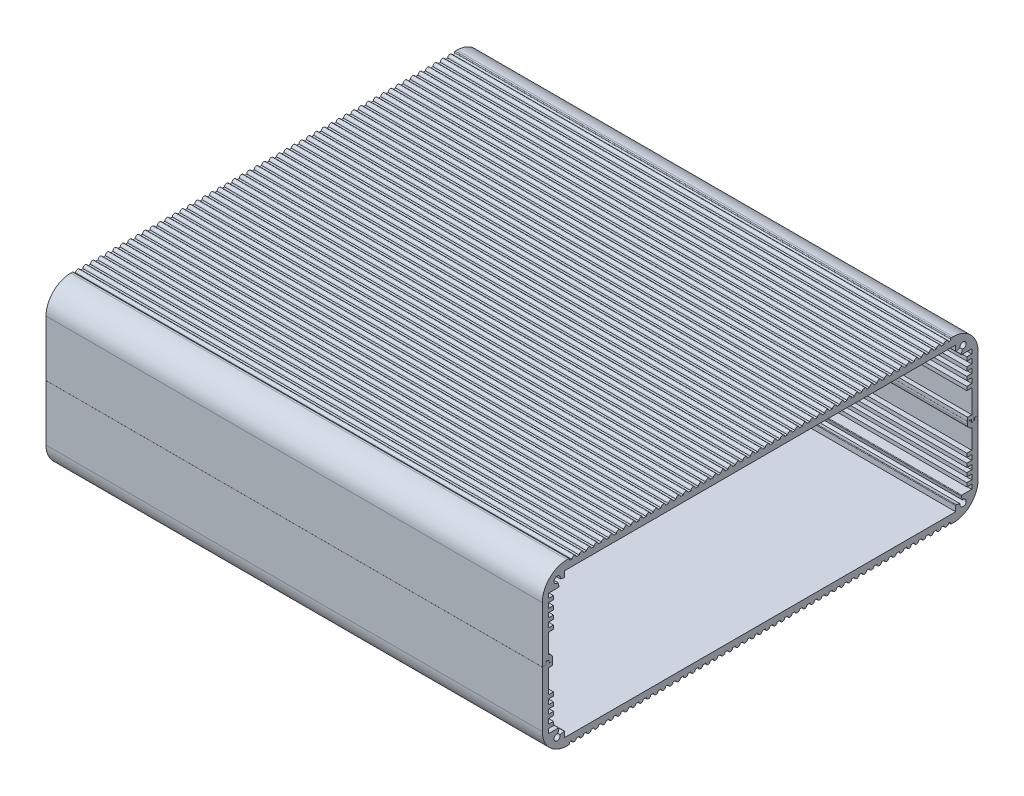
SolidWorks part; units mm, degrees
material "6063-T5"
ref_plane "前视" through (0, 0, 0) normal (0, 0, 1) x (1, 0, 0)
ref_plane "上视" through (0, 0, 0) normal (0, 1, 0) x (1, 0, 0)
ref_plane "右视" through (0, 0, 0) normal (1, 0, 0) x (0, 0, -1)
sketch "草图1" plane through (0, 0, 0) normal (1, 0, 0) x (0, 0, -1)
  line L0 (-85.55, 1.21) -> (-85.85, 1.21)
  line L1 (-86.35, 0.71) -> (-86.35, 0.01)
  line L2 (-86.35, 0.01) -> (-87.8, 0.01)
  line L3 (-87.8, 0.01) -> (-87.8, 22.51)
  line L4 (-77.8, 32.51) -> (-77.1, 32.51)
  line L5 (-76.8, 32.21) -> (-76.8, 32.11)
  line L6 (-76.3, 31.61) -> (-75.9, 31.61)
  line L7 (-74.1, 31.61) -> (-72.9, 31.61)
  line L8 (-71.1, 31.61) -> (-69.9, 31.61)
  line L9 (-68.1, 31.61) -> (-66.9, 31.61)
  line L10 (-65.1, 31.61) -> (-63.9, 31.61)
  line L11 (-62.1, 31.61) -> (-60.9, 31.61)
  line L12 (-59.1, 31.61) -> (-57.9, 31.61)
  line L13 (-56.1, 31.61) -> (-54.9, 31.61)
  line L14 (-53.1, 31.61) -> (-51.9, 31.61)
  line L15 (-50.1, 31.61) -> (-48.9, 31.61)
  line L16 (-47.1, 31.61) -> (-45.9, 31.61)
  line L17 (-44.1, 31.61) -> (-42.9, 31.61)
  line L18 (-41.1, 31.61) -> (-39.9, 31.61)
  line L19 (-38.1, 31.61) -> (-36.9, 31.61)
  line L20 (-35.1, 31.61) -> (-33.9, 31.61)
  line L21 (-32.1, 31.61) -> (-30.9, 31.61)
  line L22 (-29.1, 31.61) -> (-27.9, 31.61)
  line L23 (-26.1, 31.61) -> (-24.9, 31.61)
  line L24 (-23.1, 31.61) -> (-21.9, 31.61)
  line L25 (-20.1, 31.61) -> (-18.9, 31.61)
  line L26 (-17.1, 31.61) -> (-15.9, 31.61)
  line L27 (-14.1, 31.61) -> (-12.9, 31.61)
  line L28 (-11.1, 31.61) -> (-9.9, 31.61)
  line L29 (-8.1, 31.61) -> (-6.9, 31.61)
  line L30 (-5.1, 31.61) -> (-3.9, 31.61)
  line L31 (-2.1, 31.61) -> (-0.9, 31.61)
  line L32 (0.9, 31.61) -> (2.1, 31.61)
  line L33 (3.9, 31.61) -> (5.1, 31.61)
  line L34 (6.9, 31.61) -> (8.1, 31.61)
  line L35 (9.9, 31.61) -> (11.1, 31.61)
  line L36 (12.9, 31.61) -> (14.1, 31.61)
  line L37 (15.9, 31.61) -> (17.1, 31.61)
  line L38 (18.9, 31.61) -> (20.1, 31.61)
  line L39 (21.9, 31.61) -> (23.1, 31.61)
  line L40 (24.9, 31.61) -> (26.1, 31.61)
  line L41 (27.9, 31.61) -> (29.1, 31.61)
  line L42 (30.9, 31.61) -> (32.1, 31.61)
  line L43 (33.9, 31.61) -> (35.1, 31.61)
  line L44 (36.9, 31.61) -> (38.1, 31.61)
  line L45 (39.9, 31.61) -> (41.1, 31.61)
  line L46 (42.9, 31.61) -> (44.1, 31.61)
  line L47 (45.9, 31.61) -> (47.1, 31.61)
  line L48 (48.9, 31.61) -> (50.1, 31.61)
  line L49 (51.9, 31.61) -> (53.1, 31.61)
  line L50 (54.9, 31.61) -> (56.1, 31.61)
  line L51 (57.9, 31.61) -> (59.1, 31.61)
  line L52 (60.9, 31.61) -> (62.1, 31.61)
  line L53 (63.9, 31.61) -> (65.1, 31.61)
  line L54 (66.9, 31.61) -> (68.1, 31.61)
  line L55 (69.9, 31.61) -> (71.1, 31.61)
  line L56 (72.9, 31.61) -> (74.1, 31.61)
  line L57 (75.9, 31.61) -> (76.3, 31.61)
  line L58 (76.8, 32.11) -> (76.8, 32.21)
  line L59 (77.1, 32.51) -> (77.8, 32.51)
  line L60 (87.8, 22.51) -> (87.8, 0.01)
  line L61 (87.8, 0.01) -> (86.25, 0.01)
  line L62 (86.25, 0.01) -> (86.25, -0.69)
  line L63 (85.75, -1.19) -> (85.65, -1.19)
  line L64 (85.15, -0.69) -> (85.15, 0.01)
  line L65 (85.15, 0.01) -> (83.6, 0.01)
  line L66 (83.6, 0.01) -> (83.6, 1.51)
  line L67 (83.6, 1.51) -> (85.3, 1.51)
  line L68 (85.3, 1.51) -> (85.3, 10.91)
  line L69 (85.3, 10.91) -> (83.3, 10.91)
  line L70 (83.3, 10.91) -> (83.3, 12.41)
  line L71 (83.3, 12.41) -> (85.3, 12.41)
  line L72 (85.3, 12.41) -> (85.3, 14.41)
  line L73 (85.3, 14.41) -> (83.3, 14.41)
  line L74 (83.3, 14.41) -> (83.3, 15.91)
  line L75 (83.3, 15.91) -> (85.3, 15.91)
  line L76 (85.3, 15.91) -> (85.3, 17.71)
  line L77 (85.3, 17.71) -> (83.3, 17.71)
  line L78 (83.3, 17.71) -> (83.3, 19.21)
  line L79 (83.3, 19.21) -> (85.3, 19.21)
  line L80 (85.3, 19.21) -> (85.3, 21.21)
  line L81 (85.3, 21.21) -> (83.3, 21.21)
  line L82 (83.3, 21.21) -> (83.3, 22.71)
  line L83 (83.3, 22.71) -> (85.3, 22.71)
  line L84 (85.3, 22.71) -> (85.3, 24.51)
  line L85 (85.3, 24.51) -> (81.2568, 24.51)
  line L86 (81.0636, 24.7618) -> (81.4765, 26.3026)
  line L87 (80.5926, 27.1865) -> (79.0518, 26.7736)
  line L88 (78.8, 26.9668) -> (78.8, 29.11)
  line L89 (78.8, 29.11) -> (-78.8, 29.11)
  line L90 (-78.8, 29.11) -> (-78.8, 26.9668)
  line L91 (-79.0518, 26.7736) -> (-80.5926, 27.1865)
  line L92 (-81.4765, 26.3026) -> (-81.0636, 24.7618)
  line L93 (-81.2568, 24.51) -> (-85.3, 24.51)
  line L94 (-85.3, 24.51) -> (-85.3, 22.71)
  line L95 (-85.3, 22.71) -> (-83.3, 22.71)
  line L96 (-83.3, 22.71) -> (-83.3, 21.21)
  line L97 (-83.3, 21.21) -> (-85.3, 21.21)
  line L98 (-85.3, 21.21) -> (-85.3, 19.21)
  line L99 (-85.3, 19.21) -> (-83.3, 19.21)
  line L100 (-83.3, 19.21) -> (-83.3, 17.71)
  line L101 (-83.3, 17.71) -> (-85.3, 17.71)
  line L102 (-85.3, 17.71) -> (-85.3, 15.91)
  line L103 (-85.3, 15.91) -> (-83.3, 15.91)
  line L104 (-83.3, 15.91) -> (-83.3, 14.41)
  line L105 (-83.3, 14.41) -> (-85.3, 14.41)
  line L106 (-85.3, 14.41) -> (-85.3, 12.41)
  line L107 (-85.3, 12.41) -> (-83.3, 12.41)
  line L108 (-83.3, 12.41) -> (-83.3, 10.91)
  line L109 (-83.3, 10.91) -> (-85.3, 10.91)
  line L110 (-85.3, 10.91) -> (-85.3, 3.01)
  line L111 (-83.6, 1.0326) -> (-83.6, 0.01)
  line L112 (-83.6, 0.01) -> (-85.05, 0.01)
  line L113 (-85.05, 0.01) -> (-85.05, 0.71)
  line L114 (85.55, -1.21) -> (85.85, -1.21)
  line L115 (86.35, -0.71) -> (86.35, -0.01)
  line L116 (86.35, -0.01) -> (87.8, -0.01)
  line L117 (87.8, -0.01) -> (87.8, -22.51)
  line L118 (77.8, -32.51) -> (77.1, -32.51)
  line L119 (76.8, -32.21) -> (76.8, -32.11)
  line L120 (76.3, -31.61) -> (75.9, -31.61)
  line L121 (74.1, -31.61) -> (72.9, -31.61)
  line L122 (71.1, -31.61) -> (69.9, -31.61)
  line L123 (68.1, -31.61) -> (66.9, -31.61)
  line L124 (65.1, -31.61) -> (63.9, -31.61)
  line L125 (62.1, -31.61) -> (60.9, -31.61)
  line L126 (59.1, -31.61) -> (57.9, -31.61)
  line L127 (56.1, -31.61) -> (54.9, -31.61)
  line L128 (53.1, -31.61) -> (51.9, -31.61)
  line L129 (50.1, -31.61) -> (48.9, -31.61)
  line L130 (47.1, -31.61) -> (45.9, -31.61)
  line L131 (44.1, -31.61) -> (42.9, -31.61)
  line L132 (41.1, -31.61) -> (39.9, -31.61)
  line L133 (38.1, -31.61) -> (36.9, -31.61)
  line L134 (35.1, -31.61) -> (33.9, -31.61)
  line L135 (32.1, -31.61) -> (30.9, -31.61)
  line L136 (29.1, -31.61) -> (27.9, -31.61)
  line L137 (26.1, -31.61) -> (24.9, -31.61)
  line L138 (23.1, -31.61) -> (21.9, -31.61)
  line L139 (20.1, -31.61) -> (18.9, -31.61)
  line L140 (17.1, -31.61) -> (15.9, -31.61)
  line L141 (14.1, -31.61) -> (12.9, -31.61)
  line L142 (11.1, -31.61) -> (9.9, -31.61)
  line L143 (8.1, -31.61) -> (6.9, -31.61)
  line L144 (5.1, -31.61) -> (3.9, -31.61)
  line L145 (2.1, -31.61) -> (0.9, -31.61)
  line L146 (-0.9, -31.61) -> (-2.1, -31.61)
  line L147 (-3.9, -31.61) -> (-5.1, -31.61)
  line L148 (-6.9, -31.61) -> (-8.1, -31.61)
  line L149 (-9.9, -31.61) -> (-11.1, -31.61)
  line L150 (-12.9, -31.61) -> (-14.1, -31.61)
  line L151 (-15.9, -31.61) -> (-17.1, -31.61)
  line L152 (-18.9, -31.61) -> (-20.1, -31.61)
  line L153 (-21.9, -31.61) -> (-23.1, -31.61)
  line L154 (-24.9, -31.61) -> (-26.1, -31.61)
  line L155 (-27.9, -31.61) -> (-29.1, -31.61)
  line L156 (-30.9, -31.61) -> (-32.1, -31.61)
  line L157 (-33.9, -31.61) -> (-35.1, -31.61)
  line L158 (-36.9, -31.61) -> (-38.1, -31.61)
  line L159 (-39.9, -31.61) -> (-41.1, -31.61)
  line L160 (-42.9, -31.61) -> (-44.1, -31.61)
  line L161 (-45.9, -31.61) -> (-47.1, -31.61)
  line L162 (-48.9, -31.61) -> (-50.1, -31.61)
  line L163 (-51.9, -31.61) -> (-53.1, -31.61)
  line L164 (-54.9, -31.61) -> (-56.1, -31.61)
  line L165 (-57.9, -31.61) -> (-59.1, -31.61)
  line L166 (-60.9, -31.61) -> (-62.1, -31.61)
  line L167 (-63.9, -31.61) -> (-65.1, -31.61)
  line L168 (-66.9, -31.61) -> (-68.1, -31.61)
  line L169 (-69.9, -31.61) -> (-71.1, -31.61)
  line L170 (-72.9, -31.61) -> (-74.1, -31.61)
  line L171 (-75.9, -31.61) -> (-76.3, -31.61)
  line L172 (-76.8, -32.11) -> (-76.8, -32.21)
  line L173 (-77.1, -32.51) -> (-77.8, -32.51)
  line L174 (-87.8, -22.51) -> (-87.8, -0.01)
  line L175 (-87.8, -0.01) -> (-86.25, -0.01)
  line L176 (-86.25, -0.01) -> (-86.25, 0.69)
  line L177 (-85.75, 1.19) -> (-85.65, 1.19)
  line L178 (-85.15, 0.69) -> (-85.15, -0.01)
  line L179 (-85.15, -0.01) -> (-83.6, -0.01)
  line L180 (-83.6, -0.01) -> (-83.6, -1.51)
  line L181 (-83.6, -1.51) -> (-85.3, -1.51)
  line L182 (-85.3, -1.51) -> (-85.3, -10.91)
  line L183 (-85.3, -10.91) -> (-83.3, -10.91)
  line L184 (-83.3, -10.91) -> (-83.3, -12.41)
  line L185 (-83.3, -12.41) -> (-85.3, -12.41)
  line L186 (-85.3, -12.41) -> (-85.3, -14.41)
  line L187 (-85.3, -14.41) -> (-83.3, -14.41)
  line L188 (-83.3, -14.41) -> (-83.3, -15.91)
  line L189 (-83.3, -15.91) -> (-85.3, -15.91)
  line L190 (-85.3, -15.91) -> (-85.3, -17.71)
  line L191 (-85.3, -17.71) -> (-83.3, -17.71)
  line L192 (-83.3, -17.71) -> (-83.3, -19.21)
  line L193 (-83.3, -19.21) -> (-85.3, -19.21)
  line L194 (-85.3, -19.21) -> (-85.3, -21.21)
  line L195 (-85.3, -21.21) -> (-83.3, -21.21)
  line L196 (-83.3, -21.21) -> (-83.3, -22.71)
  line L197 (-83.3, -22.71) -> (-85.3, -22.71)
  line L198 (-85.3, -22.71) -> (-85.3, -24.51)
  line L199 (-85.3, -24.51) -> (-81.2568, -24.51)
  line L200 (-81.0636, -24.7618) -> (-81.4765, -26.3026)
  line L201 (-80.5926, -27.1865) -> (-79.0518, -26.7736)
  line L202 (-78.8, -26.9668) -> (-78.8, -29.11)
  line L203 (-78.8, -29.11) -> (78.8, -29.11)
  line L204 (78.8, -29.11) -> (78.8, -26.9668)
  line L205 (79.0518, -26.7736) -> (80.5926, -27.1865)
  line L206 (81.4765, -26.3026) -> (81.0636, -24.7618)
  line L207 (81.2568, -24.51) -> (85.3, -24.51)
  line L208 (85.3, -24.51) -> (85.3, -22.71)
  line L209 (85.3, -22.71) -> (83.3, -22.71)
  line L210 (83.3, -22.71) -> (83.3, -21.21)
  line L211 (83.3, -21.21) -> (85.3, -21.21)
  line L212 (85.3, -21.21) -> (85.3, -19.21)
  line L213 (85.3, -19.21) -> (83.3, -19.21)
  line L214 (83.3, -19.21) -> (83.3, -17.71)
  line L215 (83.3, -17.71) -> (85.3, -17.71)
  line L216 (85.3, -17.71) -> (85.3, -15.91)
  line L217 (85.3, -15.91) -> (83.3, -15.91)
  line L218 (83.3, -15.91) -> (83.3, -14.41)
  line L219 (83.3, -14.41) -> (85.3, -14.41)
  line L220 (85.3, -14.41) -> (85.3, -12.41)
  line L221 (85.3, -12.41) -> (83.3, -12.41)
  line L222 (83.3, -12.41) -> (83.3, -10.91)
  line L223 (83.3, -10.91) -> (85.3, -10.91)
  line L224 (85.3, -10.91) -> (85.3, -3.01)
  line L225 (83.6, -1.0326) -> (83.6, -0.01)
  line L226 (83.6, -0.01) -> (85.05, -0.01)
  line L227 (85.05, -0.01) -> (85.05, -0.71)
  line L228 (-81.8, 27.51) -> (81.8, -27.51) construction
  arc A0 (-85.85, 1.21) -> (-86.35, 0.71) centre (-85.85, 0.71) ccw
  arc A1 (-77.8, 32.51) -> (-87.8, 22.51) centre (-77.8, 22.51) ccw
  arc A2 (-76.8, 32.21) -> (-77.1, 32.51) centre (-77.1, 32.21) ccw
  arc A3 (-76.8, 32.11) -> (-76.3, 31.61) centre (-76.3, 32.11) ccw
  arc A4 (-74.1, 31.61) -> (-75.9, 31.61) centre (-75, 31.61) ccw
  arc A5 (-71.1, 31.61) -> (-72.9, 31.61) centre (-72, 31.61) ccw
  arc A6 (-68.1, 31.61) -> (-69.9, 31.61) centre (-69, 31.61) ccw
  arc A7 (-65.1, 31.61) -> (-66.9, 31.61) centre (-66, 31.61) ccw
  arc A8 (-62.1, 31.61) -> (-63.9, 31.61) centre (-63, 31.61) ccw
  arc A9 (-59.1, 31.61) -> (-60.9, 31.61) centre (-60, 31.61) ccw
  arc A10 (-56.1, 31.61) -> (-57.9, 31.61) centre (-57, 31.61) ccw
  arc A11 (-53.1, 31.61) -> (-54.9, 31.61) centre (-54, 31.61) ccw
  arc A12 (-50.1, 31.61) -> (-51.9, 31.61) centre (-51, 31.61) ccw
  arc A13 (-47.1, 31.61) -> (-48.9, 31.61) centre (-48, 31.61) ccw
  arc A14 (-44.1, 31.61) -> (-45.9, 31.61) centre (-45, 31.61) ccw
  arc A15 (-41.1, 31.61) -> (-42.9, 31.61) centre (-42, 31.61) ccw
  arc A16 (-38.1, 31.61) -> (-39.9, 31.61) centre (-39, 31.61) ccw
  arc A17 (-35.1, 31.61) -> (-36.9, 31.61) centre (-36, 31.61) ccw
  arc A18 (-32.1, 31.61) -> (-33.9, 31.61) centre (-33, 31.61) ccw
  arc A19 (-29.1, 31.61) -> (-30.9, 31.61) centre (-30, 31.61) ccw
  arc A20 (-26.1, 31.61) -> (-27.9, 31.61) centre (-27, 31.61) ccw
  arc A21 (-23.1, 31.61) -> (-24.9, 31.61) centre (-24, 31.61) ccw
  arc A22 (-20.1, 31.61) -> (-21.9, 31.61) centre (-21, 31.61) ccw
  arc A23 (-17.1, 31.61) -> (-18.9, 31.61) centre (-18, 31.61) ccw
  arc A24 (-14.1, 31.61) -> (-15.9, 31.61) centre (-15, 31.61) ccw
  arc A25 (-11.1, 31.61) -> (-12.9, 31.61) centre (-12, 31.61) ccw
  arc A26 (-8.1, 31.61) -> (-9.9, 31.61) centre (-9, 31.61) ccw
  arc A27 (-5.1, 31.61) -> (-6.9, 31.61) centre (-6, 31.61) ccw
  arc A28 (-2.1, 31.61) -> (-3.9, 31.61) centre (-3, 31.61) ccw
  arc A29 (0.9, 31.61) -> (-0.9, 31.61) centre (0, 31.61) ccw
  arc A30 (3.9, 31.61) -> (2.1, 31.61) centre (3, 31.61) ccw
  arc A31 (6.9, 31.61) -> (5.1, 31.61) centre (6, 31.61) ccw
  arc A32 (9.9, 31.61) -> (8.1, 31.61) centre (9, 31.61) ccw
  arc A33 (12.9, 31.61) -> (11.1, 31.61) centre (12, 31.61) ccw
  arc A34 (15.9, 31.61) -> (14.1, 31.61) centre (15, 31.61) ccw
  arc A35 (18.9, 31.61) -> (17.1, 31.61) centre (18, 31.61) ccw
  arc A36 (21.9, 31.61) -> (20.1, 31.61) centre (21, 31.61) ccw
  arc A37 (24.9, 31.61) -> (23.1, 31.61) centre (24, 31.61) ccw
  arc A38 (27.9, 31.61) -> (26.1, 31.61) centre (27, 31.61) ccw
  arc A39 (30.9, 31.61) -> (29.1, 31.61) centre (30, 31.61) ccw
  arc A40 (33.9, 31.61) -> (32.1, 31.61) centre (33, 31.61) ccw
  arc A41 (36.9, 31.61) -> (35.1, 31.61) centre (36, 31.61) ccw
  arc A42 (39.9, 31.61) -> (38.1, 31.61) centre (39, 31.61) ccw
  arc A43 (42.9, 31.61) -> (41.1, 31.61) centre (42, 31.61) ccw
  arc A44 (45.9, 31.61) -> (44.1, 31.61) centre (45, 31.61) ccw
  arc A45 (48.9, 31.61) -> (47.1, 31.61) centre (48, 31.61) ccw
  arc A46 (51.9, 31.61) -> (50.1, 31.61) centre (51, 31.61) ccw
  arc A47 (54.9, 31.61) -> (53.1, 31.61) centre (54, 31.61) ccw
  arc A48 (57.9, 31.61) -> (56.1, 31.61) centre (57, 31.61) ccw
  arc A49 (60.9, 31.61) -> (59.1, 31.61) centre (60, 31.61) ccw
  arc A50 (63.9, 31.61) -> (62.1, 31.61) centre (63, 31.61) ccw
  arc A51 (66.9, 31.61) -> (65.1, 31.61) centre (66, 31.61) ccw
  arc A52 (69.9, 31.61) -> (68.1, 31.61) centre (69, 31.61) ccw
  arc A53 (72.9, 31.61) -> (71.1, 31.61) centre (72, 31.61) ccw
  arc A54 (75.9, 31.61) -> (74.1, 31.61) centre (75, 31.61) ccw
  arc A55 (76.3, 31.61) -> (76.8, 32.11) centre (76.3, 32.11) ccw
  arc A56 (77.1, 32.51) -> (76.8, 32.21) centre (77.1, 32.21) ccw
  arc A57 (87.8, 22.51) -> (77.8, 32.51) centre (77.8, 22.51) ccw
  arc A58 (85.75, -1.19) -> (86.25, -0.69) centre (85.75, -0.69) ccw
  arc A59 (85.15, -0.69) -> (85.65, -1.19) centre (85.65, -0.69) ccw
  arc A60 (81.0636, 24.7618) -> (81.2568, 24.51) centre (81.2568, 24.71) ccw
  arc A61 (81.4765, 26.3026) -> (80.5926, 27.1865) centre (81.8, 27.51) ccw
  arc A62 (78.8, 26.9668) -> (79.0518, 26.7736) centre (79, 26.9668) ccw
  arc A63 (-79.0518, 26.7736) -> (-78.8, 26.9668) centre (-79, 26.9668) ccw
  arc A64 (-80.5926, 27.1865) -> (-81.4765, 26.3026) centre (-81.8, 27.51) ccw
  arc A65 (-81.2568, 24.51) -> (-81.0636, 24.7618) centre (-81.2568, 24.71) ccw
  arc A66 (-83.6, 1.0326) -> (-85.3, 3.01) centre (-85.6, 1.0326) ccw
  arc A67 (-85.05, 0.71) -> (-85.55, 1.21) centre (-85.55, 0.71) ccw
  arc A68 (85.85, -1.21) -> (86.35, -0.71) centre (85.85, -0.71) ccw
  arc A69 (77.8, -32.51) -> (87.8, -22.51) centre (77.8, -22.51) ccw
  arc A70 (76.8, -32.21) -> (77.1, -32.51) centre (77.1, -32.21) ccw
  arc A71 (76.8, -32.11) -> (76.3, -31.61) centre (76.3, -32.11) ccw
  arc A72 (74.1, -31.61) -> (75.9, -31.61) centre (75, -31.61) ccw
  arc A73 (71.1, -31.61) -> (72.9, -31.61) centre (72, -31.61) ccw
  arc A74 (68.1, -31.61) -> (69.9, -31.61) centre (69, -31.61) ccw
  arc A75 (65.1, -31.61) -> (66.9, -31.61) centre (66, -31.61) ccw
  arc A76 (62.1, -31.61) -> (63.9, -31.61) centre (63, -31.61) ccw
  arc A77 (59.1, -31.61) -> (60.9, -31.61) centre (60, -31.61) ccw
  arc A78 (56.1, -31.61) -> (57.9, -31.61) centre (57, -31.61) ccw
  arc A79 (53.1, -31.61) -> (54.9, -31.61) centre (54, -31.61) ccw
  arc A80 (50.1, -31.61) -> (51.9, -31.61) centre (51, -31.61) ccw
  arc A81 (47.1, -31.61) -> (48.9, -31.61) centre (48, -31.61) ccw
  arc A82 (44.1, -31.61) -> (45.9, -31.61) centre (45, -31.61) ccw
  arc A83 (41.1, -31.61) -> (42.9, -31.61) centre (42, -31.61) ccw
  arc A84 (38.1, -31.61) -> (39.9, -31.61) centre (39, -31.61) ccw
  arc A85 (35.1, -31.61) -> (36.9, -31.61) centre (36, -31.61) ccw
  arc A86 (32.1, -31.61) -> (33.9, -31.61) centre (33, -31.61) ccw
  arc A87 (29.1, -31.61) -> (30.9, -31.61) centre (30, -31.61) ccw
  arc A88 (26.1, -31.61) -> (27.9, -31.61) centre (27, -31.61) ccw
  arc A89 (23.1, -31.61) -> (24.9, -31.61) centre (24, -31.61) ccw
  arc A90 (20.1, -31.61) -> (21.9, -31.61) centre (21, -31.61) ccw
  arc A91 (17.1, -31.61) -> (18.9, -31.61) centre (18, -31.61) ccw
  arc A92 (14.1, -31.61) -> (15.9, -31.61) centre (15, -31.61) ccw
  arc A93 (11.1, -31.61) -> (12.9, -31.61) centre (12, -31.61) ccw
  arc A94 (8.1, -31.61) -> (9.9, -31.61) centre (9, -31.61) ccw
  arc A95 (5.1, -31.61) -> (6.9, -31.61) centre (6, -31.61) ccw
  arc A96 (2.1, -31.61) -> (3.9, -31.61) centre (3, -31.61) ccw
  arc A97 (-0.9, -31.61) -> (0.9, -31.61) centre (0, -31.61) ccw
  arc A98 (-3.9, -31.61) -> (-2.1, -31.61) centre (-3, -31.61) ccw
  arc A99 (-6.9, -31.61) -> (-5.1, -31.61) centre (-6, -31.61) ccw
  arc A100 (-9.9, -31.61) -> (-8.1, -31.61) centre (-9, -31.61) ccw
  arc A101 (-12.9, -31.61) -> (-11.1, -31.61) centre (-12, -31.61) ccw
  arc A102 (-15.9, -31.61) -> (-14.1, -31.61) centre (-15, -31.61) ccw
  arc A103 (-18.9, -31.61) -> (-17.1, -31.61) centre (-18, -31.61) ccw
  arc A104 (-21.9, -31.61) -> (-20.1, -31.61) centre (-21, -31.61) ccw
  arc A105 (-24.9, -31.61) -> (-23.1, -31.61) centre (-24, -31.61) ccw
  arc A106 (-27.9, -31.61) -> (-26.1, -31.61) centre (-27, -31.61) ccw
  arc A107 (-30.9, -31.61) -> (-29.1, -31.61) centre (-30, -31.61) ccw
  arc A108 (-33.9, -31.61) -> (-32.1, -31.61) centre (-33, -31.61) ccw
  arc A109 (-36.9, -31.61) -> (-35.1, -31.61) centre (-36, -31.61) ccw
  arc A110 (-39.9, -31.61) -> (-38.1, -31.61) centre (-39, -31.61) ccw
  arc A111 (-42.9, -31.61) -> (-41.1, -31.61) centre (-42, -31.61) ccw
  arc A112 (-45.9, -31.61) -> (-44.1, -31.61) centre (-45, -31.61) ccw
  arc A113 (-48.9, -31.61) -> (-47.1, -31.61) centre (-48, -31.61) ccw
  arc A114 (-51.9, -31.61) -> (-50.1, -31.61) centre (-51, -31.61) ccw
  arc A115 (-54.9, -31.61) -> (-53.1, -31.61) centre (-54, -31.61) ccw
  arc A116 (-57.9, -31.61) -> (-56.1, -31.61) centre (-57, -31.61) ccw
  arc A117 (-60.9, -31.61) -> (-59.1, -31.61) centre (-60, -31.61) ccw
  arc A118 (-63.9, -31.61) -> (-62.1, -31.61) centre (-63, -31.61) ccw
  arc A119 (-66.9, -31.61) -> (-65.1, -31.61) centre (-66, -31.61) ccw
  arc A120 (-69.9, -31.61) -> (-68.1, -31.61) centre (-69, -31.61) ccw
  arc A121 (-72.9, -31.61) -> (-71.1, -31.61) centre (-72, -31.61) ccw
  arc A122 (-75.9, -31.61) -> (-74.1, -31.61) centre (-75, -31.61) ccw
  arc A123 (-76.3, -31.61) -> (-76.8, -32.11) centre (-76.3, -32.11) ccw
  arc A124 (-77.1, -32.51) -> (-76.8, -32.21) centre (-77.1, -32.21) ccw
  arc A125 (-87.8, -22.51) -> (-77.8, -32.51) centre (-77.8, -22.51) ccw
  arc A126 (-85.75, 1.19) -> (-86.25, 0.69) centre (-85.75, 0.69) ccw
  arc A127 (-85.15, 0.69) -> (-85.65, 1.19) centre (-85.65, 0.69) ccw
  arc A128 (-81.0636, -24.7618) -> (-81.2568, -24.51) centre (-81.2568, -24.71) ccw
  arc A129 (-81.4765, -26.3026) -> (-80.5926, -27.1865) centre (-81.8, -27.51) ccw
  arc A130 (-78.8, -26.9668) -> (-79.0518, -26.7736) centre (-79, -26.9668) ccw
  arc A131 (79.0518, -26.7736) -> (78.8, -26.9668) centre (79, -26.9668) ccw
  arc A132 (80.5926, -27.1865) -> (81.4765, -26.3026) centre (81.8, -27.51) ccw
  arc A133 (81.2568, -24.51) -> (81.0636, -24.7618) centre (81.2568, -24.71) ccw
  arc A134 (83.6, -1.0326) -> (85.3, -3.01) centre (85.6, -1.0326) ccw
  arc A135 (85.05, -0.71) -> (85.55, -1.21) centre (85.55, -0.71) ccw
extrude "凸台-拉伸1" add sketch "草图1" along normal mid plane 200
